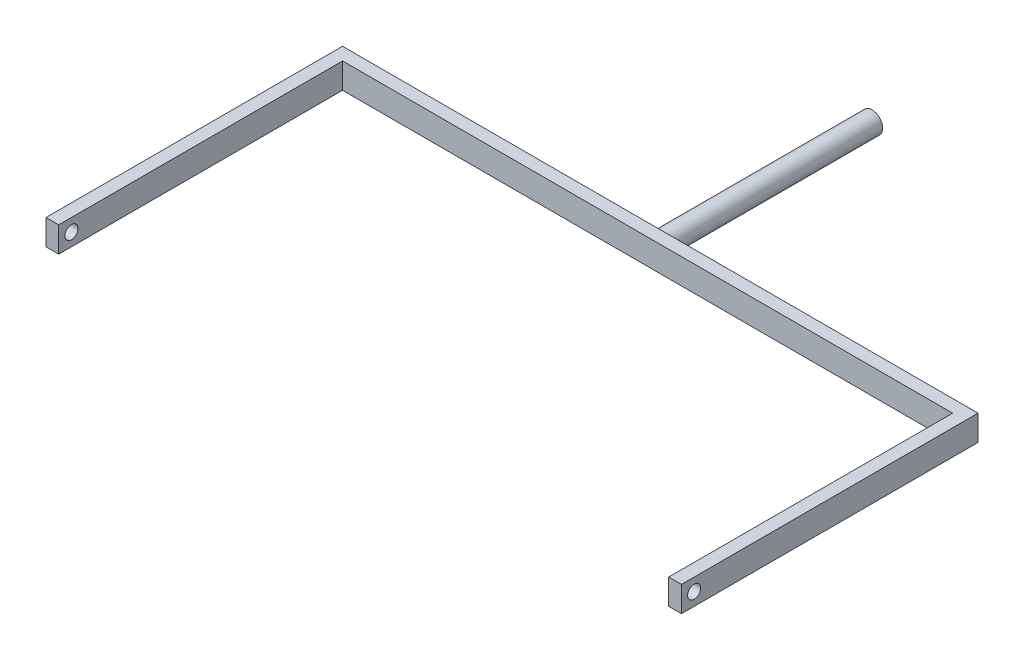
SolidWorks part; units mm, degrees
ref_plane "前视基准面" through (0, 0, 0) normal (0, 0, 1) x (1, 0, 0)
ref_plane "上视基准面" through (0, 0, 0) normal (0, 1, 0) x (1, 0, 0)
ref_plane "右视基准面" through (0, 0, 0) normal (1, 0, 0) x (0, 0, -1)
other "Configuration Table"
sketch "草图1" plane through (0, 0, 0) normal (0, 1, 0) x (1, 0, 0)
  line L0 (-72.7576, -1.4848) -> (-72.7576, -68.4848)
  line L1 (71.2424, -1.4848) -> (-72.7576, -1.4848)
  line L2 (74.2424, -1.4848) -> (74.2424, 1.5152)
  line L3 (74.2424, 1.5152) -> (-75.7576, 1.5152)
  line L4 (-75.7576, -1.4848) -> (-75.7576, 1.5152)
  line L5 (71.2424, -1.4248) -> (-75.7576, 1.5152) construction
  line L6 (74.2424, 1.5152) -> (-72.7576, -1.4848) construction
  line L7 (-75.7576, 1.5152) -> (-72.7576, 1.5152)
  line L8 (-75.7576, 1.5152) -> (-75.7576, -68.4848)
  line L9 (-75.7576, -68.4848) -> (-72.7576, -68.4848)
  line L10 (-72.7576, 1.5152) -> (-72.7576, 1.4552)
  line L11 (74.2424, 1.5152) -> (71.2424, 1.5152)
  line L12 (74.2424, 1.5152) -> (74.2424, -68.4848)
  line L13 (74.2424, -68.4848) -> (71.2424, -68.4848)
  line L14 (71.2424, 1.5152) -> (71.2424, 1.4539)
  line L15 (71.2424, -1.4248) -> (71.2424, -68.4848)
  point P0 (0, 0)
  point P12 (-72.7576, -1.4848)
  point P13 (71.2424, -1.4848)
  dimension "D1" = 150
  dimension "D2" = 3
  dimension "D3" = 3
  dimension "D4" = 70
  dimension "D5" = 70
  dimension "D6" = 3
  dimension "D7" = 67
  dimension "D8" = 67.06
  dimension "D9" = 150
  dimension "D10" = 67
extrude "凸台-拉伸2" add sketch "草图1" along normal blind 6
sketch "草图2" plane through (-72.7576, 0, 0) normal (1, 0, 0) x (0, 0, -1)
  line L0 (-68.4848, 6) -> (-68.4848, 0) construction
  line L1 (-1.4848, 0) -> (-68.4848, 0) construction
  circle A0 centre (-65.4848, 3) radius 1.55
  dimension "D2" = 3.1
  dimension "D1" = 3
  dimension "D3" = 3
extrude "切除-拉伸1" cut sketch "草图2" against normal blind 10
sketch "草图3" plane through (74.2424, 0, 0) normal (1, 0, 0) x (0, 0, -1)
  line L0 (-68.4848, 6) -> (-68.4848, 0) construction
  line L1 (1.5152, 0) -> (-68.4848, 0) construction
  circle A0 centre (-65.4848, 3) radius 1.55
  dimension "D2" = 3.1
  dimension "D1" = 3
  dimension "D3" = 3
extrude "切除-拉伸2" cut sketch "草图3" against normal blind 10 contours A0
sketch "草图5" plane through (0, 0, -1.5152) normal (0, 0, -1) x (-1, 0, 0)
  line L0 (-74.2424, 0) -> (75.7576, 0) construction
  line L1 (75.7576, 6) -> (75.7576, 0) construction
  circle A0 centre (0.7576, 3) radius 2.5
  dimension "D3" = 5
  dimension "D1" = 3
  dimension "D2" = 75
extrude "凸台-拉伸3" add sketch "草图5" along normal blind 50
